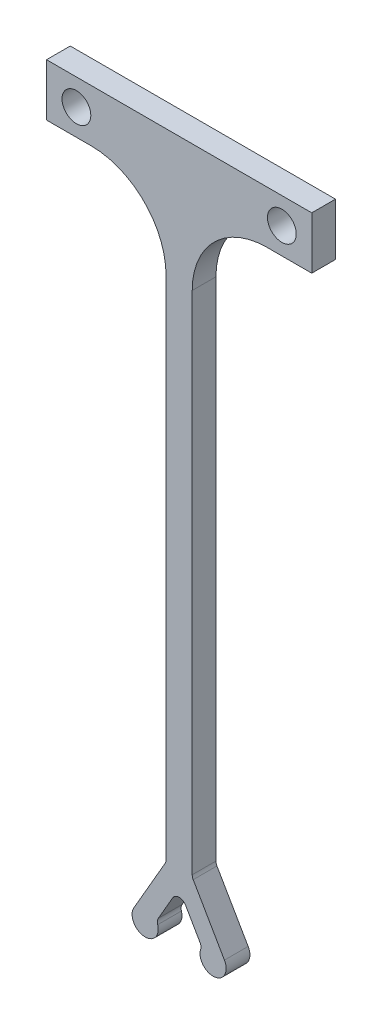
SolidWorks part; units mm, degrees
ref_plane "Front Plane" through (0, 0, 0) normal (0, 0, 1) x (1, 0, 0)
ref_plane "Top Plane" through (0, 0, 0) normal (0, 1, 0) x (1, 0, 0)
ref_plane "Right Plane" through (0, 0, 0) normal (1, 0, 0) x (0, 0, -1)
sketch "Sketch1" plane through (0, 0, 0) normal (0, 0, 1) x (1, 0, 0)
  line L0 (0, 0) -> (0, 5.25) construction
  line L1 (0, 0) -> (-9.0933, -5.25) construction
  line L2 (9.0933, -5.25) -> (0, 0) construction
  line L3 (0, 0) -> (9.5391, 0) construction
  line L4 (1.75, 90.7189) -> (17.75, 90.7189)
  line L7 (-1.884, 5.4869) -> (-6.0622, -1.75)
  line L8 (-1.75, 90.7189) -> (-17.75, 90.7189)
  line L9 (0, 5.25) -> (0, 3.25) construction
  line L10 (1.884, 5.4869) -> (6.0622, -1.75)
  line L17 (-2.783, -1.3203) -> (-0.866, 2)
  line L18 (0, 5.25) -> (-1.5155, 6.125) construction
  line L19 (-17.75, 90.7189) -> (-17.75, 83.7189)
  line L20 (-4.5466, -2.625) -> (-3.0311, -1.75) construction
  line L25 (-17.75, 83.7189) -> (-11.75, 83.7189)
  line L26 (0, 5.25) -> (1.5155, 6.125) construction
  line L27 (4.5466, -2.625) -> (3.0311, -1.75) construction
  line L28 (2.783, -1.3203) -> (0.866, 2)
  line L33 (11.75, 83.7189) -> (17.75, 83.7189)
  line L34 (1.75, 5.25) -> (-1.75, 5.25) construction
  line L36 (1.75, 5.9869) -> (1.75, 73.7189)
  line L37 (-1.75, 5.9869) -> (-1.75, 73.7189)
  line L38 (1.75, 90.7189) -> (-1.75, 90.7189)
  line L39 (17.75, 83.7189) -> (17.75, 90.7189)
  line L40 (-17.75, 87.2189) -> (17.75, 87.2189) construction
  arc A20 (-6.0622, -1.75) -> (-2.8732, -2.1129) centre (-4.5466, -2.625) ccw
  arc A21 (2.8732, -2.1129) -> (6.0622, -1.75) centre (4.5466, -2.625) ccw
  circle A22 centre (-13.75, 87.2189) radius 1.925
  circle A23 centre (13.75, 87.2189) radius 1.925
  arc A24 (-11.75, 83.7189) -> (-1.75, 73.7189) centre (-11.75, 73.7189) cw
  arc A25 (11.75, 83.7189) -> (1.75, 73.7189) centre (11.75, 73.7189) ccw
  arc A26 (0.866, 2) -> (-0.866, 2) centre (0, 1.5) ccw
  arc A27 (-2.8732, -2.1129) -> (-2.783, -1.3203) centre (-1.917, -1.8203) cw
  arc A28 (2.783, -1.3203) -> (2.8732, -2.1129) centre (1.917, -1.8203) cw
  arc A29 (-1.884, 5.4869) -> (-1.75, 5.9869) centre (-2.75, 5.9869) ccw
  arc A30 (1.884, 5.4869) -> (1.75, 5.9869) centre (2.75, 5.9869) cw
  point P10 (-4.5466, -2.625)
  point P13 (0, 5.25)
  point P39 (-1.75, 83.7189)
  point P44 (0, 3.5)
  point P53 (-1.75, 5.7189)
  point P56 (4.5466, -2.625)
  dimension "D3" = 85
  dimension "D4" = 3.5
  dimension "D5" = 120
  dimension "D15" = 16
  dimension "D16" = 16
  dimension "D17" = 7
  dimension "D18" = 3.85
  dimension "D8" = 3.5
  dimension "D12" = 3.5
  dimension "D19" = 3.85
  dimension "D22" = 10
  dimension "D23" = 1
  dimension "D24" = 1
  dimension "D25" = 1
  dimension "D26" = 1
  dimension "D27" = 1
  dimension "D1" = 120
  dimension "D2" = 120
  dimension "D7" = 120
  dimension "D9" = 2.625
  dimension "D10" = 2.625
  dimension "D11" = 7.4689
  dimension "D13" = 60
  dimension "D20" = 4
  dimension "D21" = 4
extrude "Boss-Extrude1" add sketch "Sketch1" along normal blind 3.175
